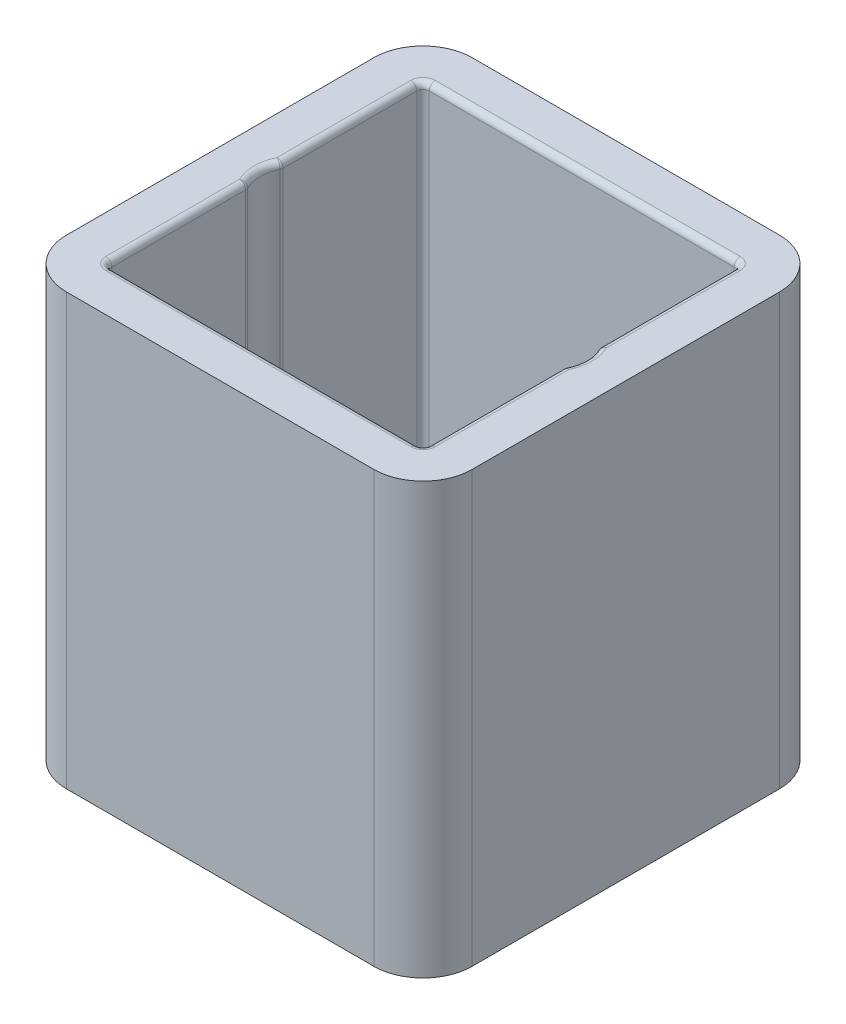
SolidWorks part; units mm, degrees
ref_plane "Ebene vorne" through (0, 0, 0) normal (0, 0, 1) x (1, 0, 0)
ref_plane "Ebene oben" through (0, 0, 0) normal (0, 1, 0) x (1, 0, 0)
ref_plane "Ebene rechts" through (0, 0, 0) normal (1, 0, 0) x (0, 0, -1)
sketch "Skizze1" plane through (0, 0, 0) normal (0, 1, 0) x (1, 0, 0)
  line L1 (-16.5, 16.5) -> (16.5, 16.5)
  line L2 (-16.5, 16.5) -> (-16.5, -16.5)
  line L3 (-16.5, -16.5) -> (16.5, -16.5)
  line L4 (16.5, 16.5) -> (16.5, -16.5)
  line L5 (-16.5, 16.5) -> (16.5, -16.5) construction
  line L6 (-16.5, -16.5) -> (16.5, 16.5) construction
  line L10 (0, 0) -> (10.25, 0) construction
  circle A0 centre (10.25, 0) radius 1.7
  circle A1 centre (5.125, -8.8768) radius 1.7
  circle A2 centre (-5.125, -8.8768) radius 1.7
  circle A3 centre (-10.25, 0) radius 1.7
  circle A4 centre (-5.125, 8.8768) radius 1.7
  circle A5 centre (5.125, 8.8768) radius 1.7
  circle A6 centre (0, 0) radius 5.5
  point P0 (0, 0)
  point P26 (0, 0)
  dimension "D3" = 10.25
  dimension "D4" = 3.4
  dimension "D1" = 33
  dimension "D5" = 6
extrude "Aufsatz-Linear austragen1" add sketch "Skizze1" against normal blind 5 contours L1 L4 L3 L2 | A3 | A4 | A5 | A0 | A2 | A1 | A6
ref_plane "Ebene1" through (0, 0, 0) normal (0, 1, 0) x (1, 0, 0)
sketch "Skizze2" plane through (0, 0, 0) normal (0, 1, 0) x (1, 0, 0)
  line L0 (12.9, 12.9) -> (7.5926, 12.9)
  line L1 (-12.9, 12.9) -> (-12.9, 3.9055)
  line L2 (-12.9, -12.9) -> (-7.5926, -12.9)
  line L3 (12.9, -12.9) -> (12.9, -3.9055)
  line L4 (-16.5, 16.5) -> (-16.5, -16.5)
  line L5 (-16.5, -16.5) -> (16.5, -16.5)
  line L6 (16.5, -16.5) -> (16.5, 16.5)
  line L7 (16.5, 16.5) -> (-16.5, 16.5)
  line L8 (-16.5, 16.5) -> (-16.5, -16.5)
  line L9 (-16.5, -16.5) -> (16.5, -16.5)
  line L10 (16.5, -16.5) -> (16.5, 16.5)
  line L11 (16.5, 16.5) -> (-16.5, 16.5)
  line L12 (-12.9, 3.9055) -> (-12.9, 1.4062)
  line L13 (-12.9, 12.9) -> (-12.9, -12.9) construction
  line L14 (-2.6574, 12.9) -> (-12.9, 12.9)
  line L15 (12.9, 12.9) -> (-12.9, 12.9) construction
  line L16 (7.5926, 12.9) -> (-2.6574, 12.9)
  line L17 (12.9, -3.9055) -> (12.9, -1.4062)
  line L18 (12.9, -12.9) -> (12.9, 12.9) construction
  line L19 (-7.5926, -12.9) -> (12.9, -12.9)
  line L20 (-12.9, -12.9) -> (12.9, -12.9) construction
  line L21 (-12.9, -1.4062) -> (-12.9, -12.9)
  line L23 (12.9, 1.4062) -> (12.9, 12.9)
  circle A1 centre (-5.125, -8.8768) radius 1.7 construction
  circle A2 centre (5.125, -8.8768) radius 1.7 construction
  circle A4 centre (5.125, 8.8768) radius 1.7 construction
  circle A5 centre (-5.125, 8.8768) radius 1.7 construction
  circle A7 centre (-5.125, -8.8768) radius 1.7 construction
  circle A8 centre (5.125, -8.8768) radius 1.7 construction
  circle A10 centre (5.125, 8.8768) radius 1.7 construction
  circle A11 centre (-5.125, 8.8768) radius 1.7 construction
  arc A18 (-12.9, 1.4062) -> (-12.9, -1.4062) centre (-10.25, 0) ccw
  arc A19 (12.9, -1.4062) -> (12.9, 1.4062) centre (10.25, 0) ccw
  dimension "D2" = 3.6
  dimension "D1" = 0
extrude "Aufsatz-Linear austragen2" add sketch "Skizze2" along normal blind 30
fillet "Verrundung1" radius 4 4 edges at (-16.5, 12.5, 16.5) (16.5, 12.5, 16.5) (-16.5, 12.5, -16.5) (16.5, 12.5, -16.5)
fillet "Verrundung4" radius 0.5 7 edges at (10.25, 0, 1.7) (5.125, 0, 10.5768) (-5.125, 0, 10.5768) (0, 0, 5.5) (5.125, 0, -7.1768) (-5.125, 0, -7.1768) (-10.25, 0, 1.7)
fillet "Verrundung5" radius 0.5 24 edges at (12.9, 0, 7.1531) (-12.9, 0, 7.1531) (13.25, 0, 0) (-13.25, 0, 0) (-12.9, 30, -7.1531) (-13.25, 30, 0) (-12.9, 30, 7.1531) (0, 30, 12.9) (12.9, 30, 7.1531) (13.25, 30, 0) (12.9, 30, -7.1531) (0, 30, -12.9) (0, 0, 12.9) (12.9, 0, -7.1531) (0, 0, -12.9) (-12.9, 0, -7.1531) (12.9, 15, -1.4062) (12.9, 15, 1.4062) (12.9, 15, 12.9) (-12.9, 15, 12.9) (-12.9, 15, 1.4062) (-12.9, 15, -1.4062) (12.9, 15, -12.9) (-12.9, 15, -12.9)
